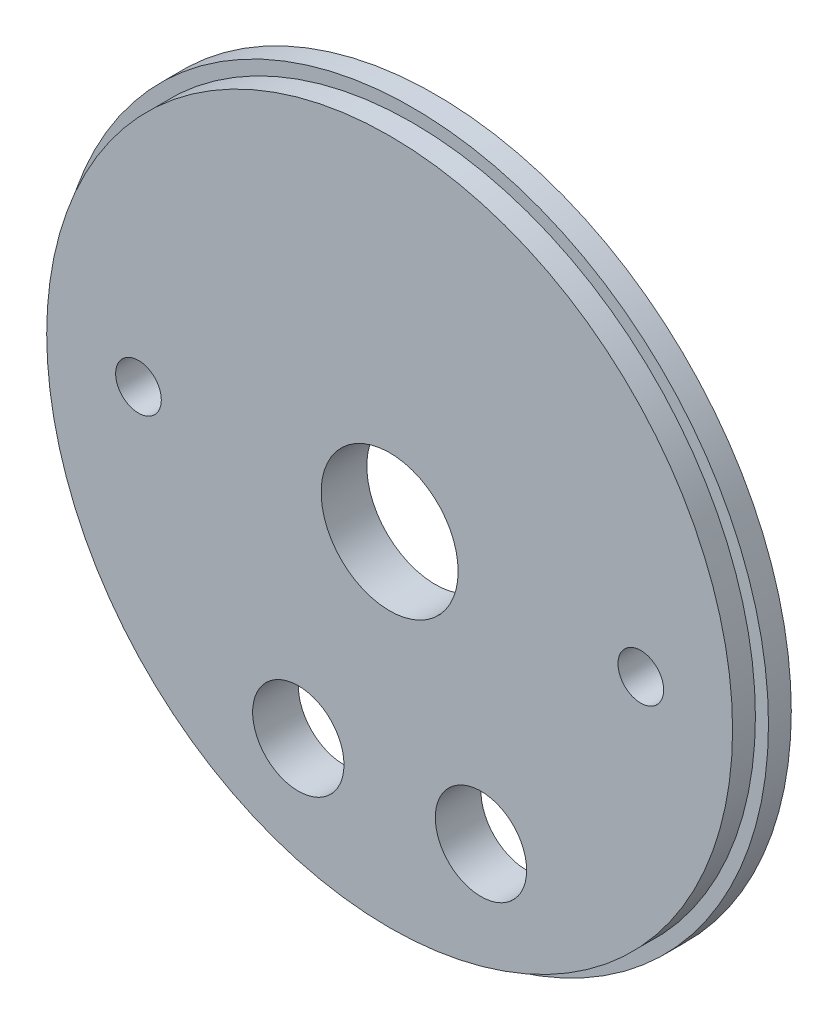
SolidWorks part; units mm, degrees
ref_plane "Front Plane" through (0, 0, 0) normal (0, 0, 1) x (1, 0, 0)
ref_plane "Top Plane" through (0, 0, 0) normal (0, 1, 0) x (1, 0, 0)
ref_plane "Right Plane" through (0, 0, 0) normal (1, 0, 0) x (0, 0, -1)
sketch "Sketch1" plane through (0, 0, 0) normal (0, 0, 1) x (1, 0, 0)
  circle A0 centre (0, 0) radius 49.5046
  dimension "D1" = 99.0092
extrude "Boss-Extrude1" add sketch "Sketch1" along normal blind 3.175
sketch "Sketch2" plane through (0, 0, 3.175) normal (0, 0, 1) x (1, 0, 0)
  circle A0 centre (0, 0) radius 47.6885
  dimension "D1" = 95.377
extrude "Boss-Extrude2" add sketch "Sketch2" along normal blind 3.175
sketch "Sketch3" plane through (0, 0, 6.35) normal (0, 0, 1) x (1, 0, 0)
  circle A0 centre (-12.7, -31.2354) radius 6.35
  circle A1 centre (12.7, -31.2354) radius 6.35
  circle A2 centre (-12.7, -31.2354) radius 12.7 construction
  circle A3 centre (-12.7, -31.2354) radius 13.97 construction
  circle A4 centre (12.7, -31.2354) radius 12.7 construction
  circle A5 centre (12.7, -31.2354) radius 13.97 construction
  circle A6 centre (0, 0) radius 47.6885 construction
  circle A7 centre (0, 0) radius 47.6885 construction
  circle A8 centre (-34.925, 0) radius 3.175
  circle A9 centre (34.925, 0) radius 3.175
  circle A10 centre (0, 0) radius 9.525
  dimension "D1" = 27.94
  dimension "D2" = 25.4
  dimension "D3" = 12.7
  dimension "D4" = 6.35
  dimension "D5" = 6.35
  dimension "D8" = 19.05
  dimension "D6" = 69.85
  dimension "D7" = 34.925
extrude "Cut-Extrude1" cut sketch "Sketch3" against normal through all
